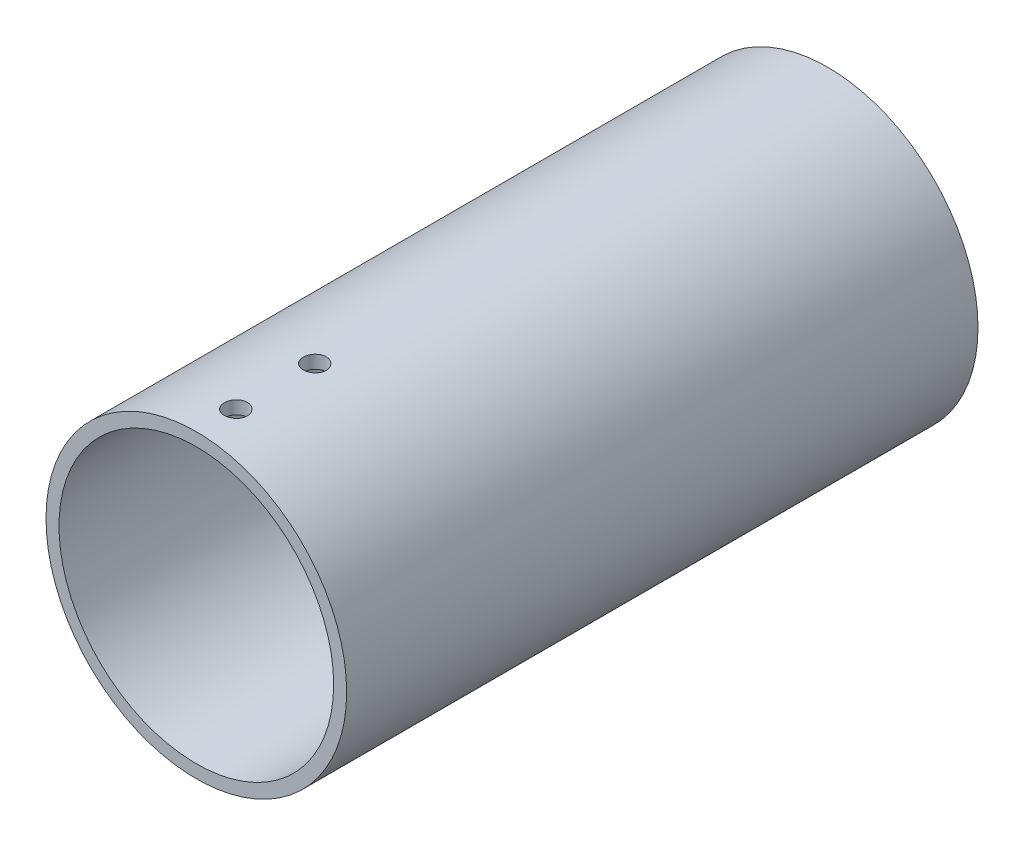
SolidWorks part; units mm, degrees
ref_plane "Front" through (0, 0, 0) normal (0, 0, 1) x (1, 0, 0)
ref_plane "Top" through (0, 0, 0) normal (0, 1, 0) x (1, 0, 0)
ref_plane "Right" through (0, 0, 0) normal (1, 0, 0) x (0, 0, -1)
sketch "Sketch1" plane through (0, 0, 0) normal (0, 0, 1) x (1, 0, 0)
  circle A0 centre (0, 0) radius 19.05
  circle A1 centre (0, 0) radius 17.4
extrude "Boss-Extrude1" add sketch "Sketch1" along normal blind 80
sketch "Sketch2" plane through (0, 0, 0) normal (0, 1, 0) x (1, 0, 0)
  line L0 (0, 0) -> (0, -73.1449) construction
  line L1 (-19.05, -80) -> (19.05, -80) construction
  circle A0 centre (0, -75) radius 1.45
  circle A1 centre (0, -65) radius 1.45
  dimension "D1" = 5
  dimension "D2" = 10
extrude "Cut-Extrude1" cut sketch "Sketch2" along normal blind 5 from offset 15
